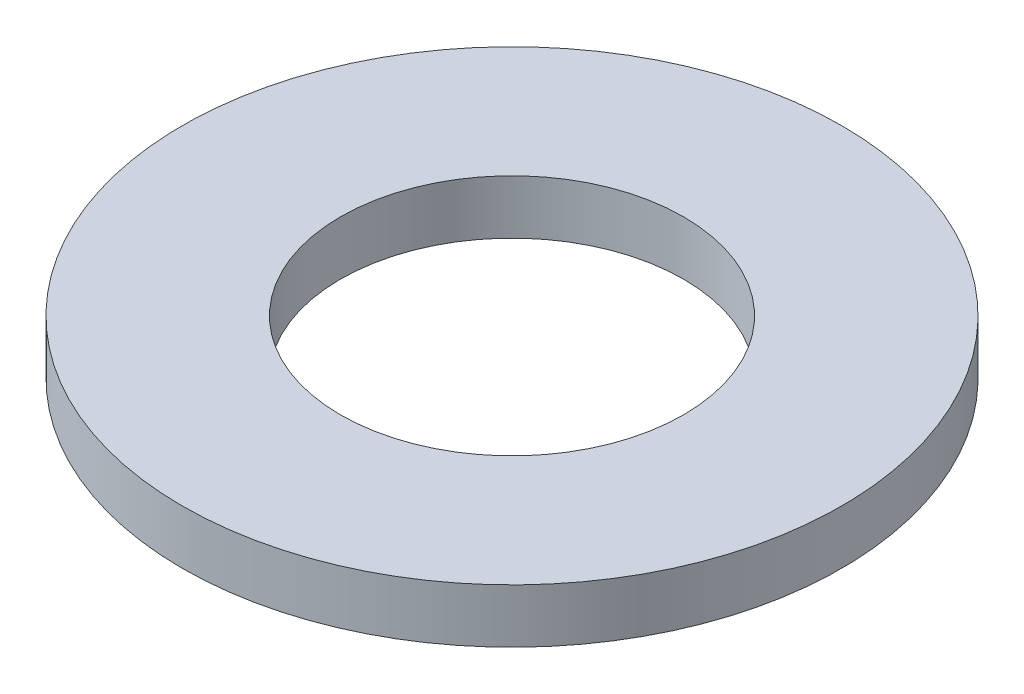
SolidWorks part; units mm, degrees
material "Alumina"
ref_plane "Front Plane" through (0, 0, 0) normal (0, 0, 1) x (1, 0, 0)
ref_plane "Top Plane" through (0, 0, 0) normal (0, 1, 0) x (1, 0, 0)
ref_plane "Right Plane" through (0, 0, 0) normal (1, 0, 0) x (0, 0, -1)
sketch "Sketch1" plane through (0, 0, 0) normal (0, 1, 0) x (1, 0, 0)
  circle A0 centre (0, 0) radius 12.2
  circle A1 centre (0, 0) radius 6.35
  dimension "D1" = 24.4
  dimension "D2" = 12.7
extrude "Boss-Extrude1" add sketch "Sketch1" along normal blind 2
